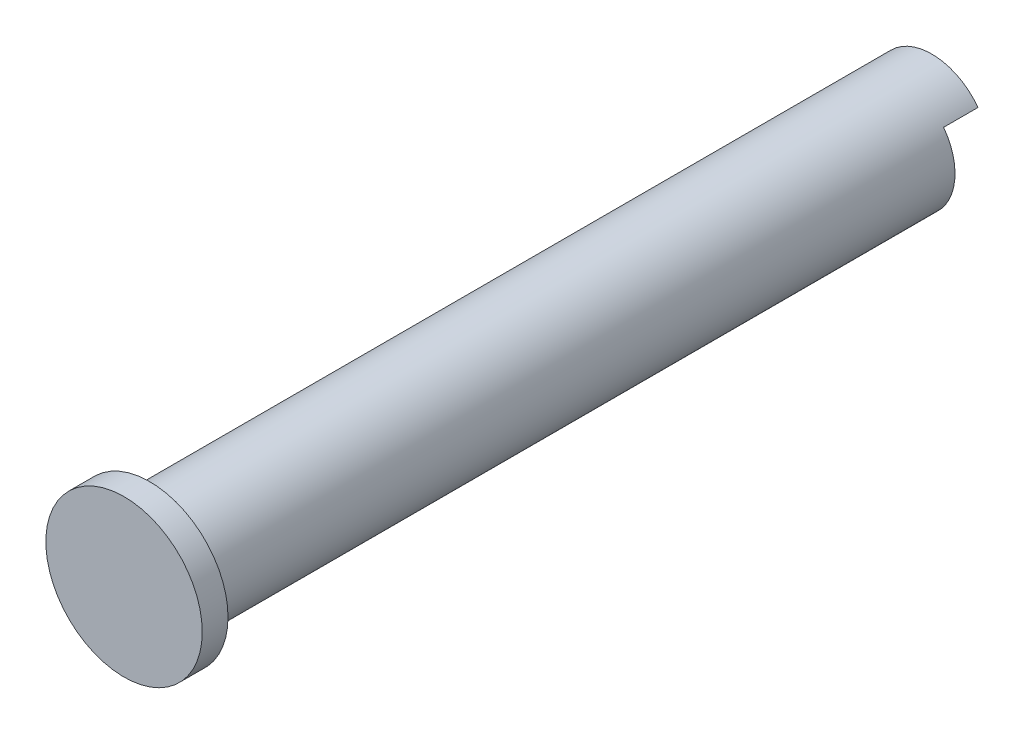
SolidWorks part; units mm, degrees
ref_plane "Plano frontal" through (0, 0, 0) normal (0, 0, 1) x (1, 0, 0)
ref_plane "Plano superior" through (0, 0, 0) normal (0, 1, 0) x (1, 0, 0)
ref_plane "Plano direito" through (0, 0, 0) normal (1, 0, 0) x (0, 0, -1)
sketch "Esboço1" plane through (0, 0, 0) normal (0, 0, 1) x (1, 0, 0)
  circle A0 centre (0, 0) radius 9.1
  dimension "D1" = 18.2
extrude "Ressalto-extrusão1" add sketch "Esboço1" against normal blind 3
sketch "Esboço2" plane through (0, 0, -3) normal (0, 0, -1) x (-1, 0, 0)
  circle A0 centre (0, 0) radius 6.7
  dimension "D1" = 13.4
extrude "Ressalto-extrusão2" add sketch "Esboço2" along normal blind 87
hole_wizard "Furo roscado para conduíte de M4x0.72" positions "Esboço5" profile "Esboço6" tap size "M4x0.7" standard "Helicoil® Metric"
sketch "Esboço5" plane through (0, 0, -90) normal (0, 0, -1) x (-1, 0, 0)
  point P0 (0, 0)
sketch "Esboço6" plane through (0, 0, -90) normal (1, 0, 0) x (0, 1, 0)
  line L0 (0, 0) -> (0, 23.2618)
  line L1 (0, 23.2618) -> (2.1, 22)
  line L2 (2.1, 22) -> (2.1, 0)
  line L5 (2.1, 0) -> (0, 0)
  line L10 (0, 23.2618) -> (-2.1, 22) construction
  line L11 (0, -6.35) -> (0, 107.95) construction
  dimension "Tap Drill Dia." = 4.2
  dimension "Tap Drill Depth" = 22
  dimension "Drill Angle" = 118
cosmetic thread "Rosca de furo2" parameters "D1"=22, "D2"=5.007
sketch "Esboço7" plane through (0, 0, -90) normal (0, 0, -1) x (-1, 0, 0)
  line L0 (0, 0) -> (0, 6.0416) construction
  line L1 (-5.3749, 4) -> (5.3749, 4)
  circle A0 centre (0, 0) radius 6.7 construction
  arc A1 (-5.3749, 4) -> (5.3749, 4) centre (0, 0) cw
  dimension "D1" = 4
extrude "Ressalto-extrusão3" add sketch "Esboço7" along normal blind 4
